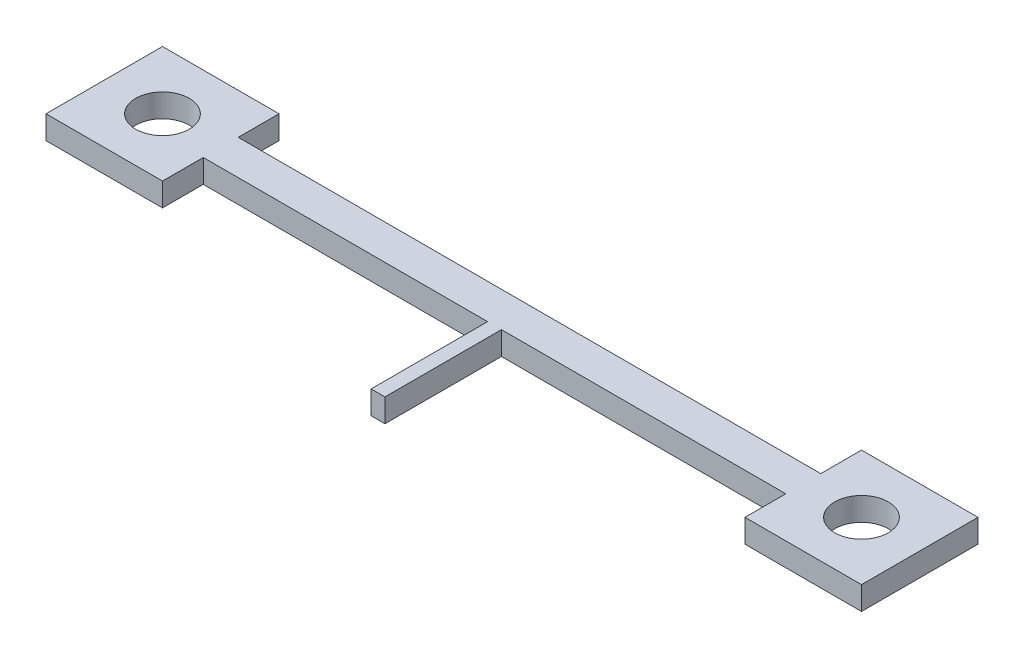
SolidWorks part; units mm, degrees
material "Commercially Pure CP-Ti UNS R50400 (SS)"
ref_plane "Front Plane" through (0, 0, 0) normal (0, 0, 1) x (1, 0, 0)
ref_plane "Top Plane" through (0, 0, 0) normal (0, 1, 0) x (1, 0, 0)
ref_plane "Right Plane" through (0, 0, 0) normal (1, 0, 0) x (0, 0, -1)
sketch "Sketch1" plane through (0, 0, 0) normal (0, 1, 0) x (1, 0, 0)
  line L0 (-41.424, -10.2833) -> (-41.424, -12.5058)
  line L1 (-47.774, -12.5058) -> (-41.424, -12.5058)
  line L2 (-47.774, -12.5058) -> (-47.774, -6.1558)
  line L3 (-47.774, -6.1558) -> (-41.424, -6.1558)
  line L4 (-3.324, -12.5058) -> (-3.324, -6.1558)
  line L7 (-41.424, -10.2833) -> (-9.674, -10.2833)
  line L9 (-41.424, -8.3783) -> (-9.674, -8.3783)
  line L13 (-41.424, -8.3783) -> (-41.424, -6.1558)
  line L14 (-9.674, -8.3783) -> (-9.674, -6.1558)
  line L15 (-9.674, -10.2833) -> (-9.674, -12.5058)
  line L16 (-9.674, -6.1558) -> (-3.324, -6.1558)
  line L17 (-9.674, -12.5058) -> (-3.324, -12.5058)
  point P0 (0, 0)
  point P6 (0, 0)
  dimension "D1" = 44.45
  dimension "D2" = 6.35
  dimension "D3" = 6.35
  dimension "D4" = 1.905
extrude "Boss-Extrude1" add sketch "Sketch1" along normal mid plane 1.27
hole_wizard "#97 (0.0059) Diameter Hole1" positions "Sketch4" profile "Sketch3" hole size "#97" standard "Ansi Inch" end condition through all
sketch "Sketch4" plane through (0, 0.635, 0) normal (0, 1, 0) x (-1, 0, 0)
  line L0 (47.774, 12.5058) -> (41.424, 6.1558) construction
  point P0 (44.599, 9.3308)
sketch "Sketch3" plane through (-44.599, 0.635, 9.3308) normal (1, 0, 0) x (0, 0, 1)
  line L0 (0, 0) -> (0, 1.27)
  line L1 (0, 1.27) -> (1.4605, 1.27)
  line L2 (1.4605, 1.27) -> (1.4605, 0)
  line L5 (1.4605, 0) -> (0, 0)
  line L11 (0, -6.35) -> (0, 107.95) construction
  dimension "Thru Hole Dia." = 2.921
  dimension "Thru Hole Depth" = 1.27
ref_plane "Plane1" through (-25.549, 0, 0) normal (1, 0, 0) x (0, 0, -1)
mirror "Mirror1" about plane through (-25.549, 0, 0) normal (1, 0, 0) of "#97 (0.0059) Diameter Hole1"
sketch "Sketch7" plane through (0, 0, 10.2833) normal (0, 0, 1) x (1, 0, 0)
  line L1 (-41.424, 0.635) -> (-9.674, 0.635) construction
  line L3 (-25.799, 0.635) -> (-25.299, 0.635)
  line L4 (-25.299, -0.635) -> (-25.799, -0.635)
  line L5 (-41.424, -0.635) -> (-9.674, -0.635) construction
  line L6 (-25.799, -0.635) -> (-25.799, 0.635)
  line L7 (-25.299, 0.635) -> (-25.299, -0.635)
extrude "Boss-Extrude2" add sketch "Sketch7" along normal blind 6.35
sketch "Sketch11" plane through (-25.799, 0, 0) normal (-1, 0, 0) x (0, 0, 1)
  line L1 (10.2833, 0.635) -> (16.6333, 0.635)
  line L2 (10.2833, 0.635) -> (10.2833, -0.635)
  line L3 (10.2833, -0.635) -> (16.6333, -0.635)
  line L4 (16.6333, 0.635) -> (16.6333, -0.635)
extrude "Boss-Extrude3" add sketch "Sketch11" along normal blind 0.127
sketch "Sketch12" plane through (-25.299, 0, 0) normal (1, 0, 0) x (0, 0, -1)
  line L1 (-10.2833, 0.635) -> (-16.6333, 0.635)
  line L2 (-10.2833, 0.635) -> (-10.2833, -0.635)
  line L3 (-10.2833, -0.635) -> (-16.6333, -0.635)
  line L4 (-16.6333, 0.635) -> (-16.6333, -0.635)
extrude "Boss-Extrude4" add sketch "Sketch12" along normal blind 0.127
